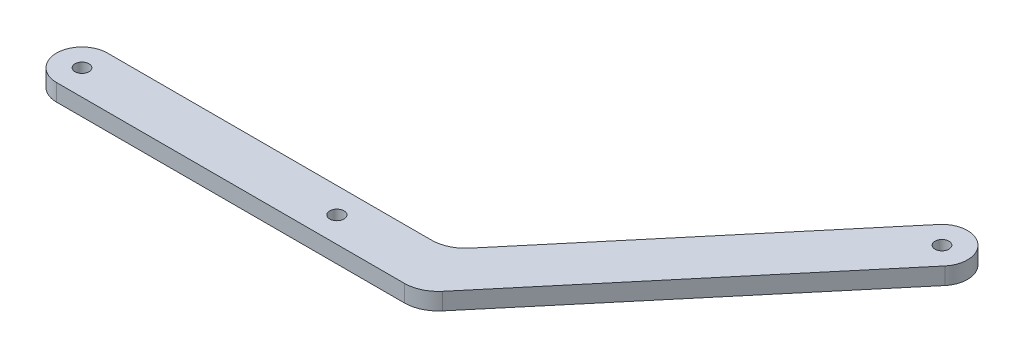
SolidWorks part; units mm, degrees
ref_plane "Front Plane" through (0, 0, 0) normal (0, 0, 1) x (1, 0, 0)
ref_plane "Top Plane" through (0, 0, 0) normal (0, 1, 0) x (1, 0, 0)
ref_plane "Right Plane" through (0, 0, 0) normal (1, 0, 0) x (0, 0, -1)
sketch "Sketch2" plane through (0, 0, 0) normal (0, 1, 0) x (1, 0, 0)
  line L0 (68.1093, 14.2756) -> (148.0947, 109.5986)
  line L1 (-62.6973, 9.739) -> (58.3806, 9.739)
  line L3 (-62.6973, -9.311) -> (64.3027, -9.311)
  line L5 (162.6879, 97.3534) -> (76.9925, -4.7744)
  line L6 (64.3027, -9.311) -> (67.2637, -9.311)
  line L7 (-62.6973, 0.214) -> (111.9385, 0.214) construction
  arc A0 (148.0947, 109.5986) -> (162.6879, 97.3534) centre (155.3913, 103.476) cw
  arc A1 (67.2637, -9.311) -> (76.9925, -4.7744) centre (67.2637, 3.389) ccw
  arc A2 (58.3806, 9.739) -> (68.1093, 14.2756) centre (58.3806, 22.439) ccw
  arc A3 (-62.6973, 9.739) -> (-62.6973, -9.311) centre (-62.6973, 0.214) ccw
  circle A4 centre (-62.6973, 0.214) radius 2.6035
  circle A5 centre (155.3913, 103.476) radius 2.6035
  circle A6 centre (32.5527, 0.214) radius 2.667
  dimension "D5" = 9.525
  dimension "D6" = 12.7
  dimension "D4" = 12.7
  dimension "D7" = 9.525
  dimension "D8" = 5.207
  dimension "D9" = 5.207
  dimension "D10" = 5.334
  dimension "D1" = 127
  dimension "D2" = 19.05
  dimension "D3" = 130
  dimension "D11" = 95.25
  dimension "D12" = 241.3
extrude "Boss-Extrude1" add sketch "Sketch2" along normal blind 6.35
